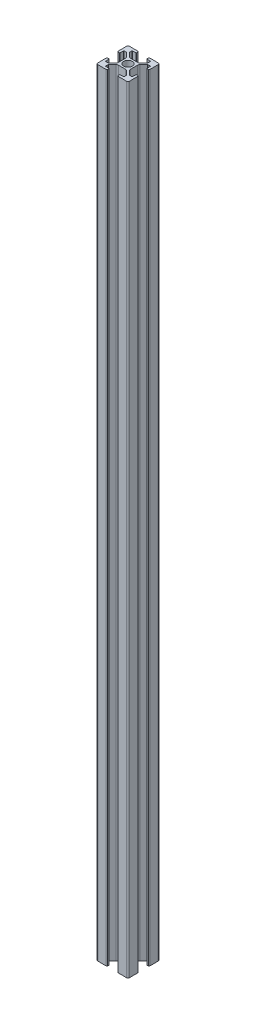
SolidWorks part; units mm, degrees
material "2014-O"
ref_plane "前视基准面" through (0, 0, 0) normal (0, 0, 1) x (1, 0, 0)
ref_plane "上视基准面" through (0, 0, 0) normal (0, 1, 0) x (1, 0, 0)
ref_plane "右视基准面" through (0, 0, 0) normal (1, 0, 0) x (0, 0, -1)
sketch "Sketch1" plane through (0, 0, 0) normal (0, 1, 0) x (1, 0, 0)
  line L1 (0, 0) -> (19.6, 0)
  line L2 (0, 0) -> (0, 19.6)
  line L3 (0, 19.6) -> (19.6, 19.6)
  line L4 (19.6, 0) -> (19.6, 19.6)
  dimension "D1" = 19.6
  dimension "D2" = 19.6
extrude "Boss-Extrude1" add sketch "Sketch1" along normal blind 480
sketch "Sketch2" plane through (0, 0, 0) normal (-1, 0, 0) x (0, 0, 1)
  line L0 (-19.6, 480) -> (0, 480) construction
  line L1 (0, 480) -> (0, 0) construction
  line L2 (-12.25, 470) -> (-12.25, 461)
  line L3 (-7.35, 470) -> (-7.35, 461)
  arc A0 (-7.35, 470) -> (-12.25, 470) centre (-9.8, 470) ccw
  arc A1 (-12.25, 461) -> (-7.35, 461) centre (-9.8, 461) ccw
  point P2 (-9.8, 480)
  dimension "D1" = 4.9
  dimension "D2" = 10
  dimension "D3" = 9.8
  dimension "D4" = 9
extrude "Cut-Extrude1" [suppressed] cut sketch "Sketch2" against normal blind 160
sketch "Sketch4" plane through (0, 0, 0) normal (0, -1, 0) x (1, 0, 0)
  line L0 (19.6, -19.6) -> (19.6, -18.6)
  line L1 (19.6, -19.6) -> (18.6, -19.6)
  line L2 (1.5, -4.3) -> (1.5, -6.35)
  line L3 (1, -19.6) -> (0, -19.6)
  line L4 (6.5092, -13.9393) -> (4.1586, -16.2899)
  line L7 (0.5, -13.05) -> (1.3, -13.05)
  line L8 (15.3, -1.5) -> (13.25, -1.5)
  line L9 (6.55, -19.1) -> (6.55, -18.3)
  line L10 (18.1, -6.35) -> (18.1, -4.3)
  line L11 (15.5, -3.1686) -> (15.5, -1.7)
  line L12 (17.9, -4.1) -> (16.4314, -4.1)
  line L13 (5.6607, -13.0908) -> (3.3101, -15.4414)
  line L14 (13.5, -7.5698) -> (13.5, -12.0302)
  line L15 (6.35, -1.5) -> (4.3, -1.5)
  line L16 (9.8, -6.1) -> (12.0302, -6.1)
  line L17 (13.0908, -5.6607) -> (15.4414, -3.3101)
  line L18 (6.1, -7.5698) -> (6.1, -12.0302)
  line L19 (7.5698, -13.5) -> (9.8, -13.5)
  line L20 (4.1, -17.9) -> (4.1, -16.4314)
  line L21 (3.1686, -15.5) -> (1.7, -15.5)
  line L22 (19.1, -6.55) -> (18.3, -6.55)
  line L23 (6.35, -18.1) -> (4.3, -18.1)
  line L24 (3.1686, -4.1) -> (1.7, -4.1)
  line L25 (1.5, -15.3) -> (1.5, -13.25)
  line L26 (4.1, -1.7) -> (4.1, -3.1686)
  line L27 (13.05, -0.5) -> (13.05, -1.3)
  line L30 (13.9393, -6.5092) -> (16.2899, -4.1586)
  line L31 (9.8, -7.15) -> (9.8, -6.1)
  line L32 (0, -19.6) -> (0, -18.6)
  line L35 (0, -1) -> (0, 0)
  line L38 (7.5698, -6.1) -> (9.8, -6.1)
  line L39 (5.6607, -6.5092) -> (3.3101, -4.1586)
  line L40 (6.55, -0.5) -> (6.55, -1.3)
  line L41 (0.5, -6.55) -> (1.3, -6.55)
  line L44 (6.5092, -5.6607) -> (4.1586, -3.3101)
  line L45 (13.9393, -13.0908) -> (16.2899, -15.4414)
  line L48 (13.05, -19.1) -> (13.05, -18.3)
  line L49 (19.1, -13.05) -> (18.3, -13.05)
  line L50 (13.0908, -13.9393) -> (15.4414, -16.2899)
  line L51 (9.8, -13.5) -> (12.0302, -13.5)
  line L52 (17.9, -15.5) -> (16.4314, -15.5)
  line L53 (15.5, -16.4314) -> (15.5, -17.9)
  line L54 (18.1, -13.25) -> (18.1, -15.3)
  line L55 (15.3, -18.1) -> (13.25, -18.1)
  line L56 (0, 0) -> (1, 0)
  line L57 (19.6, -1) -> (19.6, 0)
  line L58 (19.6, 0) -> (18.6, 0)
  line L59 (18.6, 0) -> (18.6125, -0.0199)
  line L60 (13.55, 0) -> (6.05, 0)
  line L61 (19.6, -13.55) -> (19.6, -6.05)
  line L62 (13.55, -19.6) -> (6.05, -19.6)
  line L63 (0, -6.05) -> (0, -13.55)
  arc A0 (0, -18.6) -> (1, -19.6) centre (1, -18.6) ccw
  arc A1 (6.55, -19.1) -> (6.05, -19.6) centre (6.05, -19.1) cw
  arc A2 (9.8, -7.15) -> (9.8, -12.45) centre (9.8, -9.8) ccw
  arc A3 (0.5, -13.05) -> (0, -13.55) centre (0.5, -13.55) ccw
  arc A4 (4.1, -16.4314) -> (4.1586, -16.2899) centre (4.3, -16.4314) cw
  arc A5 (3.3101, -15.4414) -> (3.1686, -15.5) centre (3.1686, -15.3) cw
  arc A6 (1.5, -15.3) -> (1.7, -15.5) centre (1.7, -15.3) ccw
  arc A7 (4.1, -17.9) -> (4.3, -18.1) centre (4.3, -17.9) ccw
  arc A8 (6.55, -18.3) -> (6.35, -18.1) centre (6.35, -18.3) ccw
  arc A9 (6.1, -12.0302) -> (5.6607, -13.0908) centre (4.6, -12.0302) cw
  arc A10 (7.5698, -13.5) -> (6.5092, -13.9393) centre (7.5698, -15) ccw
  arc A11 (1.5, -13.25) -> (1.3, -13.05) centre (1.3, -13.25) ccw
  arc A12 (13.25, -1.5) -> (13.05, -1.3) centre (13.25, -1.3) cw
  arc A13 (13.5, -7.5698) -> (13.9393, -6.5092) centre (15, -7.5698) cw
  arc A14 (12.0302, -6.1) -> (13.0908, -5.6607) centre (12.0302, -4.6) ccw
  arc A15 (18.3, -6.55) -> (18.1, -6.35) centre (18.3, -6.35) cw
  arc A16 (17.9, -4.1) -> (18.1, -4.3) centre (17.9, -4.3) cw
  arc A17 (15.3, -1.5) -> (15.5, -1.7) centre (15.3, -1.7) cw
  arc A18 (15.4414, -3.3101) -> (15.5, -3.1686) centre (15.3, -3.1686) ccw
  arc A19 (16.4314, -4.1) -> (16.2899, -4.1586) centre (16.4314, -4.3) ccw
  arc A20 (13.05, -0.5) -> (13.55, 0) centre (13.55, -0.5) cw
  arc A21 (9.8, -7.15) -> (9.8, -12.45) centre (9.8, -9.8) cw
  arc A22 (19.1, -6.55) -> (19.6, -6.05) centre (19.1, -6.05) ccw
  arc A23 (18.6, 0) -> (19.6, -1) centre (18.6, -1) cw
  arc A24 (1.5, -6.35) -> (1.3, -6.55) centre (1.3, -6.35) cw
  arc A25 (7.5698, -6.1) -> (6.5092, -5.6607) centre (7.5698, -4.6) cw
  arc A26 (6.1, -7.5698) -> (5.6607, -6.5092) centre (4.6, -7.5698) ccw
  arc A27 (6.55, -1.3) -> (6.35, -1.5) centre (6.35, -1.3) cw
  arc A28 (4.1, -1.7) -> (4.3, -1.5) centre (4.3, -1.7) cw
  arc A29 (1.5, -4.3) -> (1.7, -4.1) centre (1.7, -4.3) cw
  arc A30 (3.3101, -4.1586) -> (3.1686, -4.1) centre (3.1686, -4.3) ccw
  arc A31 (4.1, -3.1686) -> (4.1586, -3.3101) centre (4.3, -3.1686) ccw
  arc A32 (0.5, -6.55) -> (0, -6.05) centre (0.5, -6.05) cw
  arc A33 (6.55, -0.5) -> (6.05, 0) centre (6.05, -0.5) ccw
  arc A34 (0, -1) -> (1, 0) centre (1, -1) cw
  arc A35 (18.6, -19.6) -> (19.6, -18.6) centre (18.6, -18.6) ccw
  arc A36 (19.1, -13.05) -> (19.6, -13.55) centre (19.1, -13.55) cw
  arc A37 (13.05, -19.1) -> (13.55, -19.6) centre (13.55, -19.1) ccw
  arc A38 (16.4314, -15.5) -> (16.2899, -15.4414) centre (16.4314, -15.3) cw
  arc A39 (15.4414, -16.2899) -> (15.5, -16.4314) centre (15.3, -16.4314) cw
  arc A40 (15.3, -18.1) -> (15.5, -17.9) centre (15.3, -17.9) ccw
  arc A41 (17.9, -15.5) -> (18.1, -15.3) centre (17.9, -15.3) ccw
  arc A42 (18.3, -13.05) -> (18.1, -13.25) centre (18.3, -13.25) ccw
  arc A43 (12.0302, -13.5) -> (13.0908, -13.9393) centre (12.0302, -15) cw
  arc A44 (13.5, -12.0302) -> (13.9393, -13.0908) centre (15, -12.0302) ccw
  arc A45 (13.25, -18.1) -> (13.05, -18.3) centre (13.25, -18.3) ccw
  point P0 (19.1757, 0.4243)
  point P1 (-0.4243, -19.1757)
  point P2 (20.0243, -0.4243)
  point P4 (0.4243, -20.0243)
  point P12 (19.6, 0)
  point P13 (21.8458, -19.6)
  point P22 (0, -19.6)
  point P23 (0, 0)
  point P26 (20.0243, -0.4243)
  point P27 (19.1757, 0.4243)
  point P28 (0.4243, -20.0243)
  point P29 (6.55, -19.6)
  point P31 (-0.4243, -19.1757)
  point P32 (20.4243, -19.5757)
  point P33 (0.4243, 0.4243)
  point P34 (19.5757, -20.4243)
  point P35 (-0.4243, -0.4243)
  point P46 (0, -13.05)
  point P105 (13.05, 0)
  point P143 (0, -6.55)
  point P144 (6.55, 0)
  point P178 (13.05, -19.6)
  line M1 (0, 0) -> (0, -19.6)
  line M2 (0, -19.6) -> (19.6, -19.6)
  line M3 (19.6, -19.6) -> (19.6, 0)
  line M4 (19.6, 0) -> (0, 0)
  dimension "D3" = 0.5
  dimension "D2" = 1
  dimension "D5" = 0.2
  dimension "D7" = 1.5
  dimension "D8" = 0.2
  dimension "D1" = 6.55
  dimension "D4" = 6.55
extrude "Cut-Extrude3" cut sketch "Sketch4" against normal through all contours A45 L55 A40 L53 A39 L50 A43 L51 L19 A10 L4 A4 L20 A7 L23 A8 L9 A1 A37 L48 M2 | L41 A32 A3 L7 A11 L25 A6 L21 A5 L13 A9 L18 A26 L39 A30 L24 A29 L2 A24 M1 | L14 A44 L45 A38 L52 A41 L54 A42 L49 A36 A22 L22 A15 L10 A16 L12 A19 L30 A13 M3 | A33 L40 A27 L15 A28 L26 A31 L44 A25 L38 L16 A14 L17 A18 L11 A17 L8 A12 L27 A20 M4 | A23 M4 M3 | A34 M1 M4 | A21 A2 | L1 A35 L0 | L32 A0 L3
sketch "Sketch6" plane through (0, 0, -13.5) normal (0, 0, -1) x (-1, 0, 0)
  line L0 (-9.8, 480) -> (-9.8, 470) construction
  line L1 (-7.5698, 480) -> (-12.0302, 480) construction
  line L2 (-9.8, 0) -> (-9.8, 10) construction
  line L4 (-7.5698, 0) -> (-12.0302, 0) construction
  circle A0 centre (-9.8, 10) radius 2
  circle A2 centre (-9.8, 470) radius 2
  dimension "D2" = 4
  dimension "D3" = 4
  dimension "D1" = 10
  dimension "D4" = 10
extrude "Cut-Extrude5" cut sketch "Sketch6" against normal blind 10
